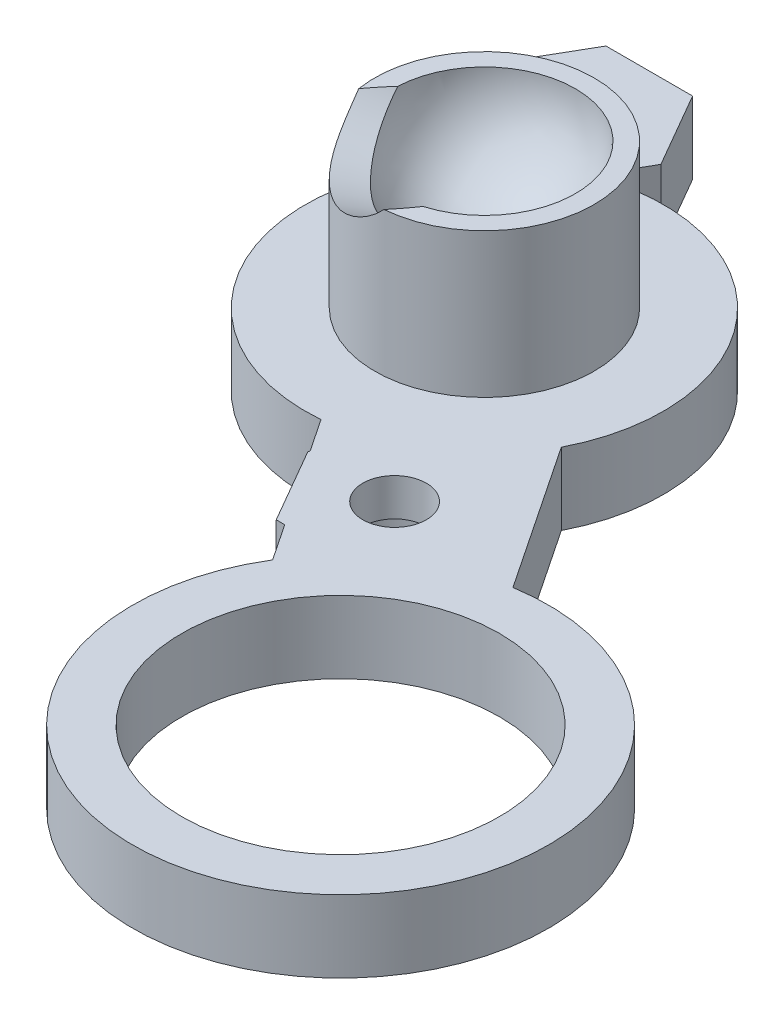
SolidWorks part; units mm, degrees
other "Compression Link 2 Moving Ball Retainer"
ref_plane "Front Plane" through (0, 0, 0) normal (0, 0, 1) x (1, 0, 0)
ref_plane "Top Plane" through (0, 0, 0) normal (0, 1, 0) x (1, 0, 0)
ref_plane "Right Plane" through (0, 0, 0) normal (1, 0, 0) x (0, 0, -1)
sketch3d "Retainer Feature 1 profile datum points"
  point P0 (-30.3109, -101, -15)
  point P1 (-20.3109, -101, -15)
  point P2 (-30.3109, -101, -5)
ref_plane "Retainer Feature 1 profile plane" through (0, -101, 0) normal (0, -1, 0) x (-1, 0, 0)
sketch "Retainer Feature 1 profile" plane through (0, -101, 0) normal (0, -1, 0) x (-1, 0, 0)
  circle A0 centre (30.3109, 15) radius 3.8
extrude "Retainer Feature 1" add sketch "Retainer Feature 1 profile" along normal blind 5.02 separate body
sketch3d "Retainer Feature 2 profile datum points"
  point P0 (-30.3109, -106, -15)
  point P1 (-20.3109, -106, -15)
  point P2 (-30.3109, -106, -5)
ref_plane "Retainer Feature 2 profile plane" through (0, -106, 0) normal (0, -1, 0) x (-1, 0, 0)
sketch "Retainer Feature 2 profile" plane through (0, -106, 0) normal (0, -1, 0) x (-1, 0, 0)
  circle A0 centre (30.3109, 15) radius 6.2
extrude "Retainer Feature 2" add sketch "Retainer Feature 2 profile" along normal blind 2.5
sketch3d "Middle Right Floating Compression Ball Retainer 2 Hexagonal Screw Pad 22 datum points"
  point P0 (-34.5609, -106, -22.3612)
  point P1 (-24.5609, -106, -22.3612)
  point P2 (-34.5609, -106, -12.3612)
ref_plane "Middle Right Floating Compression Ball Retainer 2 Hexagonal Screw Pad 22 plane" through (0, -106, 0) normal (0, -1, 0) x (-1, 0, 0)
sketch "Middle Right Floating Compression Ball Retainer 2 Hexagonal Screw Pad 22" plane through (0, -106, 0) normal (0, -1, 0) x (-1, 0, 0)
  line L0 (31.5609, 22.3612) -> (33.0609, 19.7631)
  line L1 (33.0609, 19.7631) -> (36.0609, 19.7631)
  line L2 (36.0609, 19.7631) -> (37.5609, 22.3612)
  line L3 (37.5609, 22.3612) -> (36.0609, 24.9593)
  line L4 (36.0609, 24.9593) -> (33.0609, 24.9593)
  line L5 (33.0609, 24.9593) -> (31.5609, 22.3612)
extrude "Retainer Feature 5" add sketch "Middle Right Floating Compression Ball Retainer 2 Hexagonal Screw Pad 22" along normal blind 2.5
sketch3d "Middle Right Floating Compression Ball Retainer 2 Hexagonal Screw Pad 25 datum points"
  point P0 (-26.0609, -106, -7.6388)
  point P1 (-16.0609, -106, -7.6388)
  point P2 (-26.0609, -106, 2.3612)
ref_plane "Middle Right Floating Compression Ball Retainer 2 Hexagonal Screw Pad 25 plane" through (0, -106, 0) normal (0, -1, 0) x (-1, 0, 0)
sketch "Middle Right Floating Compression Ball Retainer 2 Hexagonal Screw Pad 25" plane through (0, -106, 0) normal (0, -1, 0) x (-1, 0, 0)
  line L0 (23.0609, 7.6388) -> (24.5609, 5.0407)
  line L1 (24.5609, 5.0407) -> (27.5609, 5.0407)
  line L2 (27.5609, 5.0407) -> (29.0609, 7.6388)
  line L3 (29.0609, 7.6388) -> (27.5609, 10.2369)
  line L4 (27.5609, 10.2369) -> (24.5609, 10.2369)
  line L5 (24.5609, 10.2369) -> (23.0609, 7.6388)
extrude "Retainer Feature 8" add sketch "Middle Right Floating Compression Ball Retainer 2 Hexagonal Screw Pad 25" along normal blind 2.5
sketch3d "Retainer Feature 9 axis line"
  line L0 (-30.3109, -101, -25) -> (-30.3109, -101, -5) construction
ref_axis "Retainer Feature 9 axis" through (-30.3109, -101, -25) along (0, 0, 1)
sketch3d "Retainer Feature 9 profile datum points"
  point P0 (-30.3109, -101, -15)
  point P1 (-20.3109, -101, -15)
  point P2 (-30.3109, -101, -5)
ref_plane "Retainer Feature 9 profile plane" through (0, -101, 0) normal (0, -1, 0) x (-1, 0, 0)
sketch "Retainer Feature 9 profile" plane through (0, -101, 0) normal (0, -1, 0) x (-1, 0, 0)
  line L0 (30.3109, 11.85) -> (30.3109, 18.15)
  arc A0 (30.3109, 18.15) -> (30.3109, 11.85) centre (30.3109, 15) ccw
revolve "Retainer Feature 9" cut sketch "Retainer Feature 9 profile" angle 360 about axis through (-30.3109, -101, -25) along (0, 0, 1)
sketch3d "Middle Right Floating Compression Ball Retainer 2 Plate Sketch 114 datum points"
  point P0 (-30.3109, -106, -15)
  point P1 (-24.7565, -106, -6.6844)
  point P2 (-38.6265, -106, -9.4456)
ref_plane "Middle Right Floating Compression Ball Retainer 2 Plate Sketch 114 plane" through (0, -106, 0) normal (0, -1, 0) x (-1, 0, 0)
sketch "Middle Right Floating Compression Ball Retainer 2 Plate Sketch 114" plane through (0, -106, 0) normal (0, -1, 0) x (-1, 0, 0)
  line L0 (27.8162, 16.6663) -> (17.797, 1.6663)
  line L1 (17.797, 1.6663) -> (22.7863, -1.6663)
  line L2 (22.7863, -1.6663) -> (32.8056, 13.3337)
  line L3 (32.8056, 13.3337) -> (27.8162, 16.6663)
extrude "Retainer Feature 12" add sketch "Middle Right Floating Compression Ball Retainer 2 Plate Sketch 114" along normal blind 2.5
sketch3d "Retainer Feature 13 profile datum points"
  point P0 (-20.2917, -106, 0)
  point P1 (-10.2917, -106, 0)
  point P2 (-20.2917, -106, 10)
ref_plane "Retainer Feature 13 profile plane" through (0, -106, 0) normal (0, -1, 0) x (-1, 0, 0)
sketch "Retainer Feature 13 profile" plane through (0, -106, 0) normal (0, -1, 0) x (-1, 0, 0)
  circle A0 centre (20.2917, 0) radius 7.2
extrude "Retainer Feature 13" add sketch "Retainer Feature 13 profile" along normal blind 2.5
sketch3d "Retainer Feature 14 profile datum points"
  point P0 (-20.2917, -105.9, 0)
  point P1 (-10.2917, -105.9, 0)
  point P2 (-20.2917, -105.9, 10)
ref_plane "Retainer Feature 14 profile plane" through (0, -105.9, 0) normal (0, -1, 0) x (-1, 0, 0)
sketch "Retainer Feature 14 profile" plane through (0, -105.9, 0) normal (0, -1, 0) x (-1, 0, 0)
  circle A0 centre (20.2917, 0) radius 5.5
extrude "Retainer Feature 14" cut sketch "Retainer Feature 14 profile" along normal blind 2.7
sketch3d "Retainer Feature 15 profile datum points"
  point P0 (-34.5609, -105, -22.3612)
  point P1 (-24.5609, -105, -22.3612)
  point P2 (-34.5609, -105, -12.3612)
ref_plane "Retainer Feature 15 profile plane" through (0, -105, 0) normal (0, -1, 0) x (-1, 0, 0)
sketch "Retainer Feature 15 profile" plane through (0, -105, 0) normal (0, -1, 0) x (-1, 0, 0)
  circle A0 centre (34.5609, 22.3612) radius 1.1
extrude "Retainer Feature 15" cut sketch "Retainer Feature 15 profile" along normal blind 3.75
sketch3d "Retainer Feature 16 profile datum points"
  point P0 (-34.5609, -107.3, -22.3612)
  point P1 (-24.5609, -107.3, -22.3612)
  point P2 (-34.5609, -107.3, -12.3612)
ref_plane "Retainer Feature 16 profile plane" through (0, -107.3, 0) normal (0, -1, 0) x (-1, 0, 0)
sketch "Retainer Feature 16 profile" plane through (0, -107.3, 0) normal (0, -1, 0) x (-1, 0, 0)
  circle A0 centre (34.5609, 22.3612) radius 2.1
extrude "Retainer Feature 16" cut sketch "Retainer Feature 16 profile" along normal blind 1.45
sketch3d "Retainer Feature 17 profile datum points"
  point P0 (-26.0609, -105, -7.6388)
  point P1 (-16.0609, -105, -7.6388)
  point P2 (-26.0609, -105, 2.3612)
ref_plane "Retainer Feature 17 profile plane" through (0, -105, 0) normal (0, -1, 0) x (-1, 0, 0)
sketch "Retainer Feature 17 profile" plane through (0, -105, 0) normal (0, -1, 0) x (-1, 0, 0)
  circle A0 centre (26.0609, 7.6388) radius 1.1
extrude "Retainer Feature 17" cut sketch "Retainer Feature 17 profile" along normal blind 3.75
sketch3d "Retainer Feature 18 profile datum points"
  point P0 (-26.0609, -107.3, -7.6388)
  point P1 (-16.0609, -107.3, -7.6388)
  point P2 (-26.0609, -107.3, 2.3612)
ref_plane "Retainer Feature 18 profile plane" through (0, -107.3, 0) normal (0, -1, 0) x (-1, 0, 0)
sketch "Retainer Feature 18 profile" plane through (0, -107.3, 0) normal (0, -1, 0) x (-1, 0, 0)
  circle A0 centre (26.0609, 7.6388) radius 2.1
extrude "Retainer Feature 18" cut sketch "Retainer Feature 18 profile" along normal blind 1.45
sketch3d "Articulation Throat axis line"
  line L0 (-25.111, -106.3831, -21.632) -> (-35.5108, -95.6169, -8.368) construction
ref_axis "Articulation Throat axis" through (-25.111, -106.3831, -21.632) along (-0.52, 0.5383, 0.6632)
sketch3d "Articulation Throat Sketch datum points"
  point P0 (-30.3109, -101, -15)
  point P1 (-30.3109, -93.2358, -21.3021)
  point P2 (-35.5108, -95.6169, -8.368)
ref_plane "Articulation Throat Sketch plane" through (-55.5594, -21.3154, -26.2607) normal (0.8542, 0.3277, 0.4037) x (0.3769, 0.1446, -0.9149)
sketch "Articulation Throat Sketch" plane through (-55.5594, -21.3154, -26.2607) normal (0.8542, 0.3277, 0.4037) x (0.3769, 0.1446, -0.9149)
  line L0 (-12.3085, -83.4412) -> (-10.7241, -81.7739)
  line L1 (-10.7241, -81.7739) -> (-22.7679, -61.059)
  line L2 (-22.7679, -61.059) -> (-28.9813, -67.5977)
  line L3 (-28.9813, -67.5977) -> (-12.3085, -83.4412)
revolve "Articulation Throat" cut sketch "Articulation Throat Sketch" angle 360 about axis through (-25.111, -106.3831, -21.632) along (-0.52, 0.5383, 0.6632)
